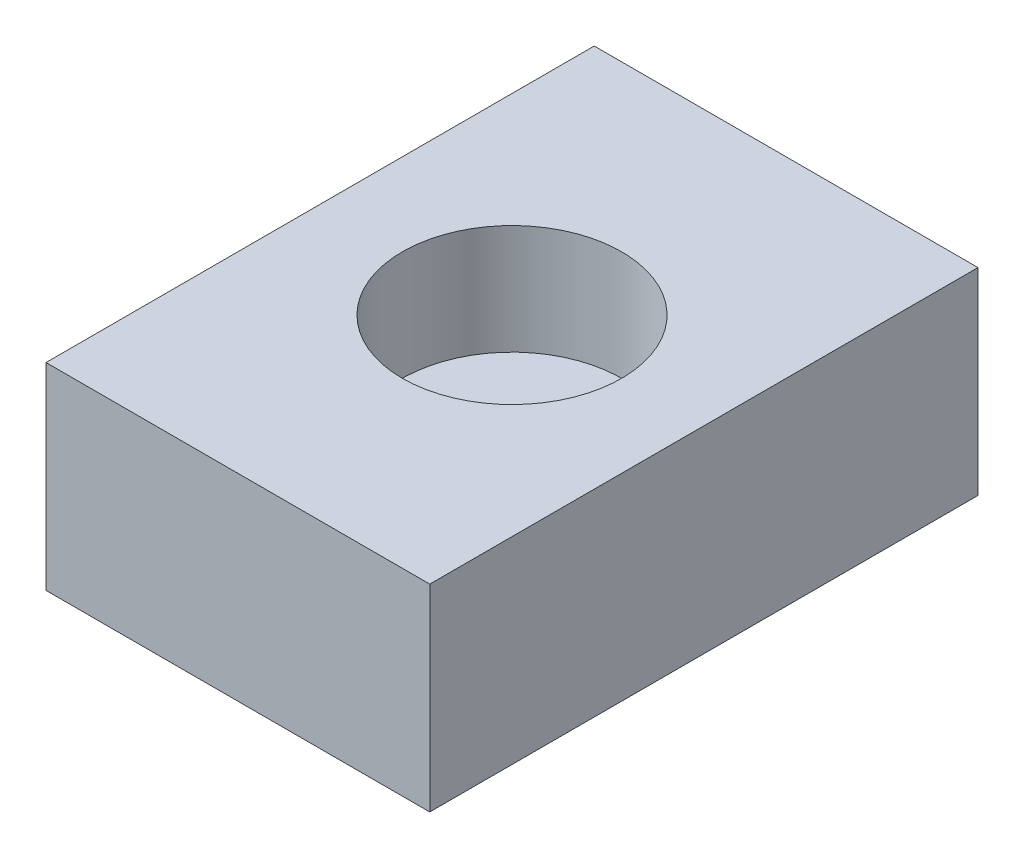
SolidWorks part; units mm, degrees
ref_plane "Front Plane" through (0, 0, 0) normal (0, 0, 1) x (1, 0, 0)
ref_plane "Top Plane" through (0, 0, 0) normal (0, 1, 0) x (1, 0, 0)
ref_plane "Right Plane" through (0, 0, 0) normal (1, 0, 0) x (0, 0, -1)
sketch "Sketch1" plane through (0, 0, 0) normal (0, 1, 0) x (1, 0, 0)
  line L1 (-17.5, -25) -> (17.5, -25)
  line L2 (-17.5, -25) -> (-17.5, 25)
  line L3 (-17.5, 25) -> (17.5, 25)
  line L4 (17.5, -25) -> (17.5, 25)
  line L5 (-17.5, -25) -> (17.5, 25) construction
  line L6 (-17.5, 25) -> (17.5, -25) construction
  point P0 (0, 0)
  dimension "D1" = 50
  dimension "D2" = 35
extrude "Boss-Extrude1" add sketch "Sketch1" along normal blind 18
sketch "Sketch3" plane through (0, 18, 0) normal (0, 1, 0) x (1, 0, 0)
  circle A0 centre (0, 0) radius 10
  dimension "D1" = 20
extrude "Cut-Extrude1" cut sketch "Sketch3" against normal blind 10
